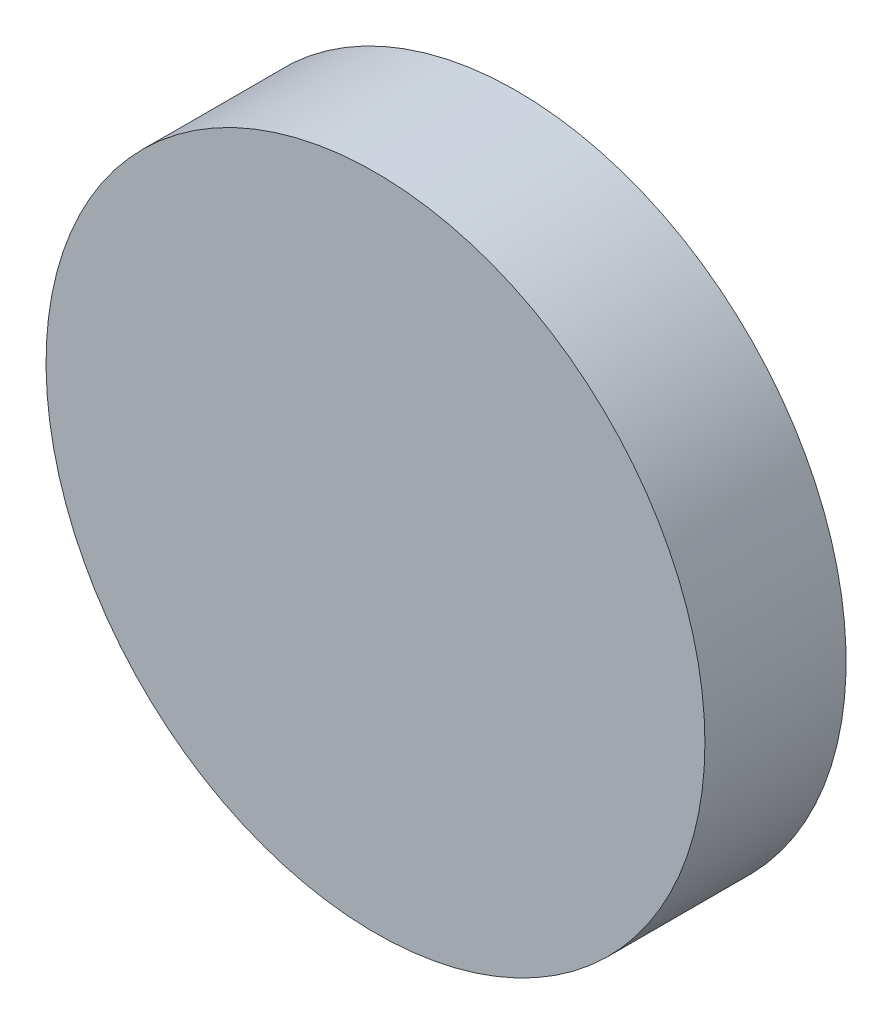
SolidWorks part; units mm, degrees
ref_plane "Front Plane" through (0, 0, 0) normal (0, 0, 1) x (1, 0, 0)
ref_plane "Top Plane" through (0, 0, 0) normal (0, 1, 0) x (1, 0, 0)
ref_plane "Right Plane" through (0, 0, 0) normal (1, 0, 0) x (0, 0, -1)
sketch "Sketch1" plane through (0, 0, 0) normal (0, 0, 1) x (1, 0, 0)
  circle A0 centre (0, 0) radius 14
  circle A1 centre (0, 0) radius 10.85
  circle A2 centre (0, 0) radius 12.65
  dimension "D1" = 21.7
  dimension "D2" = 28
  dimension "D3" = 25.3
extrude "Boss-Extrude1" add sketch "Sketch1" along normal blind 2 contours A1
sketch "Sketch2" plane through (0, 0, 2) normal (0, 0, 1) x (1, 0, 0)
  circle A0 centre (0, 0) radius 14
extrude "Boss-Extrude2" add sketch "Sketch2" along normal blind 1
sketch "Sketch3" plane through (0, 0, 2) normal (0, 0, -1) x (-1, 0, 0)
  line L1 (0, 0) -> (9.548, 10.239)
  line L3 (0, 0) -> (9.548, -10.239)
  arc A0 (8.6273, 9.2516) -> (8.6273, -9.2516) centre (0, 0) ccw
  arc A1 (9.548, 10.239) -> (9.548, -10.239) centre (0, 0) ccw
  circle A2 centre (0, 0) radius 14 construction
  circle M5 centre (0, 0) radius 14
extrude "Boss-Extrude3" add sketch "Sketch3" along normal blind 5 contours A0 L1 L3 M5
